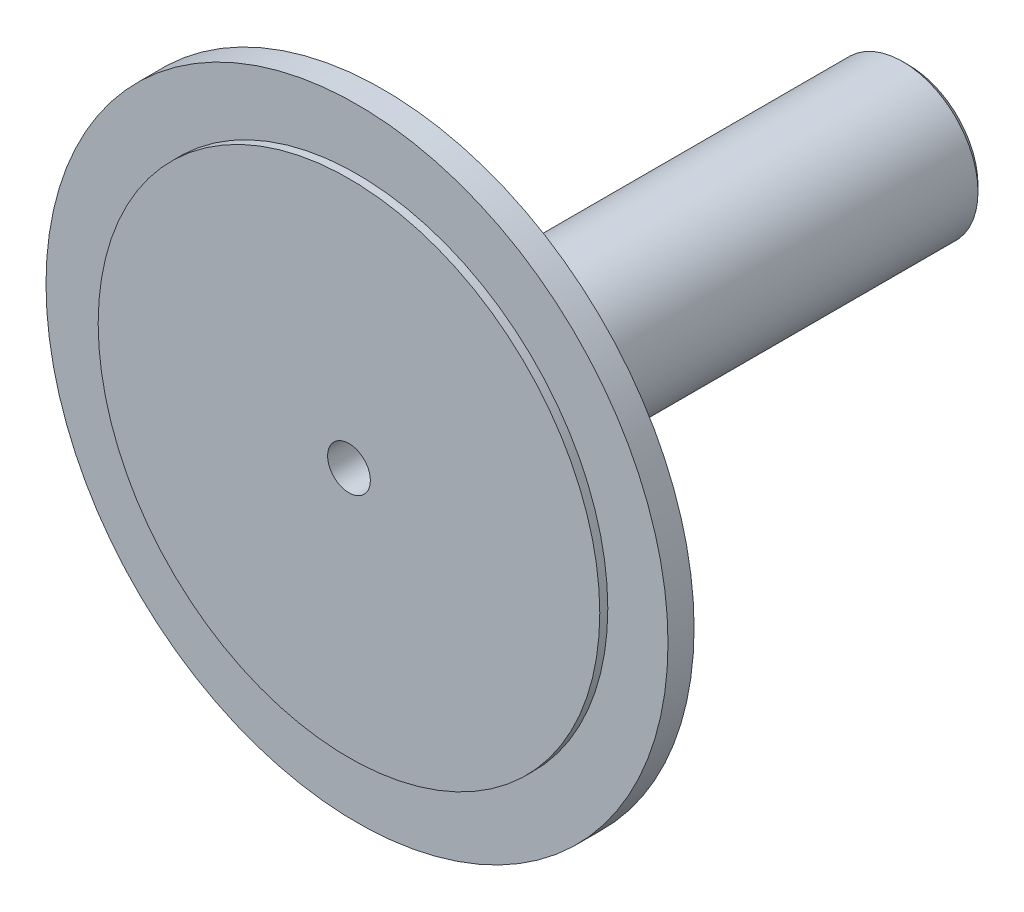
SolidWorks part; units mm, degrees
ref_plane "Primary" through (0, 0, 0) normal (0, 0, 1) x (1, 0, 0)
ref_plane "Top" through (0, 0, 0) normal (0, 1, 0) x (1, 0, 0)
ref_plane "Side" through (0, 0, 0) normal (1, 0, 0) x (0, 0, -1)
sketch "Sketch1" plane through (0, 0, 0) normal (0, 0, 1) x (1, 0, 0)
  circle A0 centre (0, 0) radius 39.37
  dimension "D1" = 78.74
extrude "Base-Extrude" add sketch "Sketch1" along normal blind 6.35
sketch "Sketch2" plane through (0, 0, 6.35) normal (0, 0, 1) x (1, 0, 0)
  circle A0 centre (0, 0) radius 31.75
  dimension "D1" = 63.5
extrude "Boss-Extrude1" add sketch "Sketch2" along normal blind 1.016
sketch "Sketch3" plane through (0, 0, 0) normal (0, 0, -1) x (-1, 0, 0)
  circle A0 centre (0, 0) radius 9.525
  dimension "D1" = 19.05
extrude "Boss-Extrude2" add sketch "Sketch3" along normal blind 63.5
chamfer "Chamfer1" distance 0.762 angle 45 2 edges at (9.525, 0, 0) (-9.525, 0, -63.5)
hole_wizard "1/4-28 Tapped Hole1" positions "Sketch6" profile "Sketch5" tap size "1/4-28" standard "Ansi Inch"
sketch "Sketch6" plane through (0, 0, 7.366) normal (0, 0, 1) x (1, 0, 0)
  point P0 (0, 0)
sketch "Sketch5" plane through (0, 0, 7.366) normal (1, 0, 0) x (0, -1, 0)
  line L0 (0, 0) -> (0, 19.05)
  line L1 (0, 19.05) -> (2.7051, 19.05)
  line L2 (2.7051, 19.05) -> (2.7051, 0)
  line L5 (2.7051, 0) -> (0, 0)
  line L10 (0, 19.05) -> (-2.7051, 19.05) construction
  line L11 (0, -6.35) -> (0, 107.95) construction
  dimension "Hole Dia." = 5.4102
  dimension "Hole Depth" = 19.05
  dimension "Drill Angle" = 180
cosmetic thread "Cosmetic Thread1" parameters "D1"=4.7625, "D2"=6.35
chamfer "Chamfer2" distance 3.048 angle 60 1 edges at (39.37, 0, 0)
